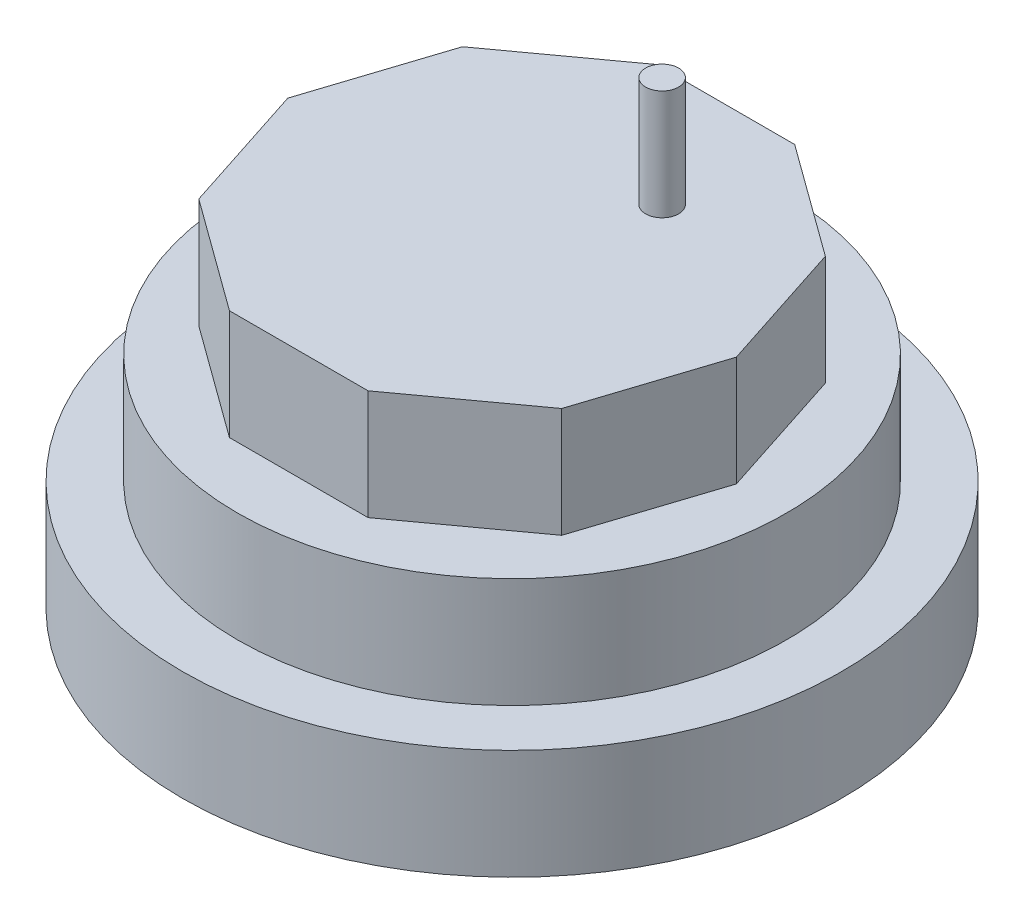
SolidWorks part; units mm, degrees
ref_plane "Front Plane" through (0, 0, 0) normal (0, 0, 1) x (1, 0, 0)
ref_plane "Top Plane" through (0, 0, 0) normal (0, 1, 0) x (1, 0, 0)
ref_plane "Right Plane" through (0, 0, 0) normal (1, 0, 0) x (0, 0, -1)
sketch "Sketch2" plane through (0, 0, 0) normal (0, 1, 0) x (1, 0, 0)
  circle A0 centre (0, 0) radius 76.2
  dimension "D1" = 152.4
extrude "Boss-Extrude1" add sketch "Sketch2" along normal blind 25.4
sketch "Sketch3" plane through (0, 25.4, 0) normal (0, 1, 0) x (1, 0, 0)
  circle A0 centre (0, 0) radius 63.5
  dimension "D1" = 127
extrude "Boss-Extrude2" add sketch "Sketch3" along normal blind 25.4
sketch "Sketch4" plane through (0, 50.8, 0) normal (0, 1, 0) x (1, 0, 0)
  line L0 (0, 63.5) -> (0, -63.5) construction
  line L2 (41.9521, -30.48) -> (51.8557, 0)
  line L3 (51.8557, 0) -> (41.9521, 30.48)
  line L4 (41.9521, 30.48) -> (16.0243, 49.3177)
  line L5 (16.0243, 49.3177) -> (-16.0243, 49.3177)
  line L6 (-16.0243, 49.3177) -> (-41.9521, 30.48)
  line L7 (-41.9521, 30.48) -> (-51.8557, 0)
  line L8 (-51.8557, 0) -> (-41.9521, -30.48)
  line L9 (-41.9521, -30.48) -> (-16.0243, -49.3177)
  line L10 (-16.0243, -49.3177) -> (16.0243, -49.3177)
  line L11 (16.0243, -49.3177) -> (41.9521, -30.48)
  circle A0 centre (0, 0) radius 63.5 construction
  circle A1 centre (0, 0) radius 63.5 construction
  circle A2 centre (0, 0) radius 49.3177 construction
  dimension "D1" = 30.48
  dimension "D2" = 90
extrude "Boss-Extrude3" add sketch "Sketch4" along normal blind 25.4
sketch "Sketch5" plane through (0, 76.2, 0) normal (0, 1, 0) x (1, 0, 0)
  line L0 (0, 49.3177) -> (0, -49.3177) construction
  line L1 (16.0243, 49.3177) -> (-16.0243, 49.3177) construction
  line L2 (-16.0243, -49.3177) -> (16.0243, -49.3177) construction
  line L3 (0, 0) -> (12.7, 21.997) construction
  circle A0 centre (12.7, 21.997) radius 3.81
  dimension "D3" = 7.62
  dimension "D1" = 30
  dimension "D2" = 25.4
extrude "Boss-Extrude4" add sketch "Sketch5" along normal blind 25.4
